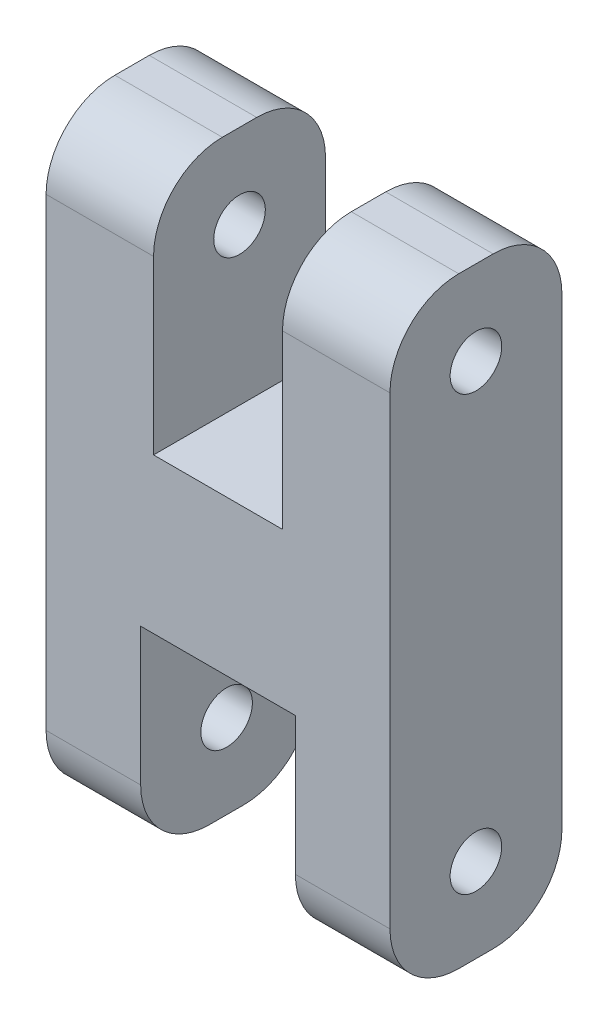
SolidWorks part; units mm, degrees
ref_plane "Alzado" through (0, 0, 0) normal (0, 0, 1) x (1, 0, 0)
ref_plane "Planta" through (0, 0, 0) normal (0, 1, 0) x (1, 0, 0)
ref_plane "Vista lateral" through (0, 0, 0) normal (1, 0, 0) x (0, 0, -1)
sketch "Croquis1" plane through (0, 0, 0) normal (1, 0, 0) x (0, 0, -1)
  line L0 (-5, 0) -> (5, 0) construction
  line L1 (-1, 17.5) -> (1, 17.5)
  line L2 (-5, 13.5) -> (-5, -13.5)
  line L3 (-1, -17.5) -> (1, -17.5)
  line L4 (5, 13.5) -> (5, -13.5)
  line L5 (-5, 17.5) -> (5, -17.5) construction
  line L6 (-5, -17.5) -> (5, 17.5) construction
  arc A0 (-5, -13.5) -> (-1, -17.5) centre (-1, -13.5) ccw
  arc A1 (1, -17.5) -> (5, -13.5) centre (1, -13.5) ccw
  arc A2 (-1, 17.5) -> (-5, 13.5) centre (-1, 13.5) ccw
  arc A3 (1, 17.5) -> (5, 13.5) centre (1, 13.5) cw
  circle A4 centre (0, 12.6) radius 1.5
  circle A5 centre (0, -12.6) radius 1.5
  point P0 (0, 0)
  dimension "D3" = 4
  dimension "D5" = 3
  dimension "D1" = 35
  dimension "D2" = 10
  dimension "D4" = 4.9
extrude "Saliente-Extruir1" add sketch "Croquis1" along normal mid plane 20
sketch "Croquis2" plane through (0, 0, 0) normal (0, 0, 1) x (1, 0, 0)
  line L5 (10, -17.5) -> (-10, -17.5) construction
  line L6 (-4.5, -17.5) -> (4.5, -17.5)
  line L7 (-4.5, -17.5) -> (-4.5, -5.5)
  line L8 (-4.5, -5.5) -> (4.5, -5.5)
  line L9 (4.5, -17.5) -> (4.5, -5.5)
  line L10 (-10, 0) -> (10, 0) construction
  line L11 (-10, 13.5) -> (-10, -13.5) construction
  line L12 (10, 13.5) -> (10, -13.5) construction
  line L13 (10, 17.5) -> (-10, 17.5) construction
  line L15 (-3.75, 17.5) -> (-3.75, 3.5)
  line L17 (3.75, 17.5) -> (3.75, 3.5)
  line L23 (-3.75, 17.5) -> (3.75, 17.5)
  line L24 (-3.75, 3.5) -> (3.75, 3.5)
  point P18 (0, -5.5)
  point P20 (0, 3.5)
  dimension "D1" = 9
  dimension "D2" = 12
  dimension "D3" = 7.5
  dimension "D4" = 14
extrude "Cortar-Extruir1" cut sketch "Croquis2" against normal through all both and the other way through all
